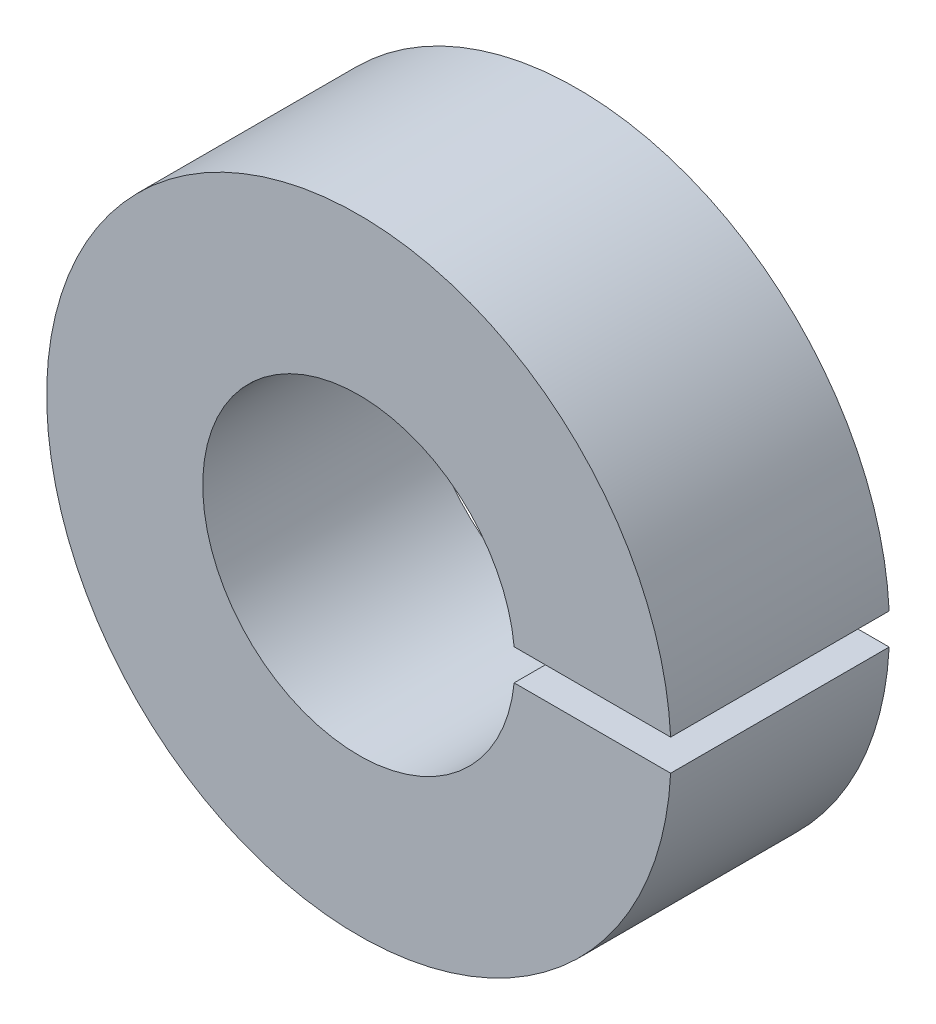
SolidWorks part; units mm, degrees
ref_plane "前视基准面" through (0, 0, 0) normal (0, 0, 1) x (1, 0, 0)
ref_plane "上视基准面" through (0, 0, 0) normal (0, 1, 0) x (1, 0, 0)
ref_plane "右视基准面" through (0, 0, 0) normal (1, 0, 0) x (0, 0, -1)
ref_plane "基准面1" through (0, 0, -7) normal (0, 0, 1) x (1, 0, 0)
sketch "草图1" plane through (0, 0, -7) normal (0, 0, 1) x (1, 0, 0)
  circle A0 centre (0, 0) radius 20
  circle A1 centre (0, 0) radius 10
extrude "凸台-拉伸1" add sketch "草图1" along normal blind 14
sketch "草图2" plane through (0, 0, -7) normal (0, 0, 1) x (1, 0, 0)
  line L0 (9, -1) -> (21, -1)
  line L1 (21, -1) -> (21, 1)
  line L2 (21, 1) -> (9, 1)
  line L3 (9, 1) -> (9, -1)
extrude "切除-拉伸1" cut sketch "草图2" along normal through all
ref_plane "基准面2" through (0, -7, 0) normal (0, 1, 0) x (1, 0, 0)
sketch "草图4" plane through (0, -7, 0) normal (0, 1, 0) x (1, 0, 0)
  circle A0 centre (15, 0) radius 2.25
extrude "切除-拉伸3" cut sketch "草图4" along normal blind 14
